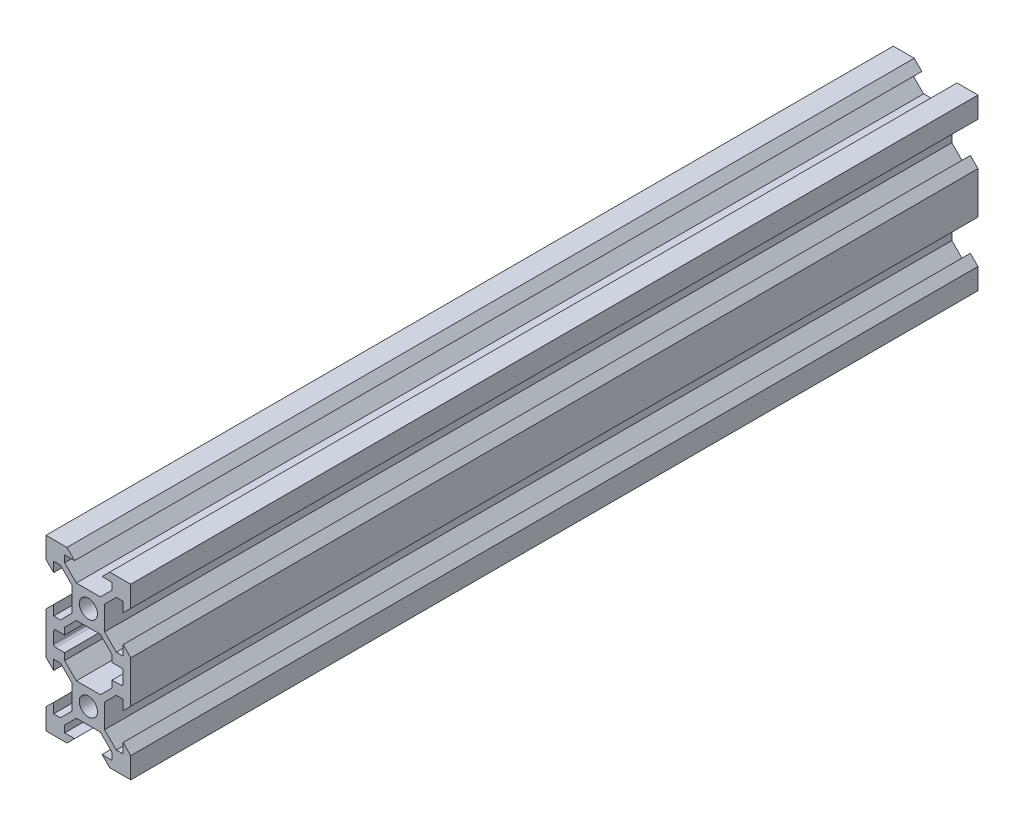
SolidWorks part; units mm, degrees
ref_plane "Alzado" through (0, 0, 0) normal (0, 0, 1) x (1, 0, 0)
ref_plane "Planta" through (0, 0, 0) normal (0, 1, 0) x (1, 0, 0)
ref_plane "Vista lateral" through (0, 0, 0) normal (1, 0, 0) x (0, 0, -1)
sketch "Croquis1" plane through (0, 0, 0) normal (0, 0, 1) x (1, 0, 0)
  line L0 (0, 0) -> (0, -20) construction
  line L2 (0, 0) -> (0, -0.5674)
  line L5 (6.175, -7.1649) -> (6.175, -12.8351)
  line L6 (7.1649, -13.825) -> (12.8351, -13.825)
  line L7 (13.825, -7.1649) -> (13.825, -12.8351)
  line L8 (7.1649, -6.175) -> (12.8351, -6.175)
  line L9 (6.175, -13.825) -> (13.825, -13.825) construction
  line L10 (13.825, -6.175) -> (13.825, -13.825) construction
  line L12 (10, -10) -> (32.1172, -10) construction
  line L13 (13.25, -18.2) -> (15.05, -20)
  line L14 (20, -20) -> (15.6, -20)
  line L15 (20, -20) -> (20, -15.6)
  line L16 (18.2, -15.6) -> (16.5899, -15.6)
  line L32 (15.6, -18.2) -> (15.6, -16.5899)
  line L33 (10, -10) -> (10, -23.2493) construction
  line L34 (4.4, -18.2) -> (4.4, -16.5899)
  line L35 (7.1649, -13.825) -> (4.4, -16.5899)
  line L36 (15.6, -18.2) -> (13.25, -18.2)
  line L38 (15.6, -20) -> (15.05, -20)
  line L40 (15.05, -20) -> (20, -20)
  line L41 (0, -20) -> (20, -20) construction
  line L42 (6.175, -12.8351) -> (3.4101, -15.6)
  line L43 (18.2, -13.25) -> (20, -15.05)
  line L44 (20, -20) -> (18.2, -20)
  line L45 (20, -20) -> (20, -15.05)
  line L48 (20, -15.05) -> (20, -20)
  line L49 (20, 0) -> (20, -20) construction
  line L50 (18.2, -15.6) -> (18.2, -13.25)
  line L51 (12.8351, -13.825) -> (15.6, -16.5899)
  line L52 (13.825, -12.8351) -> (16.5899, -15.6)
  line L53 (1.8, -15.6) -> (3.4101, -15.6)
  line L54 (1.8, -15.6) -> (1.8, -13.25)
  line L55 (1.8, -13.25) -> (0, -15.05)
  line L56 (0, 0) -> (20, 0) construction
  line L57 (0, -20) -> (0, -15.6)
  line L58 (0, -15.6) -> (0, -15.05)
  line L59 (0, -20) -> (4.4, -20)
  line L60 (0, -20) -> (4.95, -20)
  line L61 (6.75, -18.2) -> (4.95, -20)
  line L62 (4.4, -18.2) -> (6.75, -18.2)
  line L63 (1.8, -4.4) -> (3.4101, -4.4)
  line L64 (6.175, -7.1649) -> (3.4101, -4.4)
  line L65 (7.1649, -6.175) -> (4.4, -3.4101)
  line L66 (4.4, -1.8) -> (4.4, -3.4101)
  line L71 (0, 0) -> (0, -4.4)
  line L72 (0, 0) -> (0, -4.95)
  line L73 (1.8, -6.75) -> (0, -4.95)
  line L74 (1.8, -4.4) -> (1.8, -6.75)
  line L75 (15.6, -1.8) -> (15.6, -3.4101)
  line L76 (12.8351, -6.175) -> (15.6, -3.4101)
  line L77 (13.825, -7.1649) -> (16.5899, -4.4)
  line L78 (18.2, -4.4) -> (16.5899, -4.4)
  line L79 (18.2, -4.4) -> (18.2, -6.75)
  line L80 (18.2, -6.75) -> (20, -4.95)
  line L81 (20, 0) -> (20, -4.4)
  line L82 (20, -4.4) -> (20, -4.95)
  line L87 (6.175, -6.175) -> (13.825, -6.175) construction
  line L88 (6.175, -6.175) -> (6.175, -13.825) construction
  line L89 (0, 20) -> (0, 19.4326)
  line L90 (6.175, 12.8351) -> (6.175, 7.1649)
  line L91 (7.1649, 6.175) -> (12.8351, 6.175)
  line L92 (13.825, 12.8351) -> (13.825, 7.1649)
  line L93 (7.1649, 13.825) -> (12.8351, 13.825)
  line L96 (20, 0) -> (20, 4.4)
  line L97 (18.2, 4.4) -> (16.5899, 4.4)
  line L98 (15.6, 1.8) -> (15.6, 3.4101)
  line L99 (4.4, 1.8) -> (4.4, 3.4101)
  line L100 (7.1649, 6.175) -> (4.4, 3.4101)
  line L104 (6.175, 7.1649) -> (3.4101, 4.4)
  line L105 (18.2, 6.75) -> (20, 4.95)
  line L107 (20, 0) -> (20, 4.95)
  line L108 (20, 4.95) -> (20, 0)
  line L109 (18.2, 4.4) -> (18.2, 6.75)
  line L110 (12.8351, 6.175) -> (15.6, 3.4101)
  line L111 (13.825, 7.1649) -> (16.5899, 4.4)
  line L112 (1.8, 4.4) -> (3.4101, 4.4)
  line L113 (1.8, 4.4) -> (1.8, 6.75)
  line L114 (1.8, 6.75) -> (0, 4.95)
  line L115 (0, 0) -> (0, 4.4)
  line L116 (0, 4.4) -> (0, 4.95)
  line L121 (1.8, 15.6) -> (3.4101, 15.6)
  line L122 (6.175, 12.8351) -> (3.4101, 15.6)
  line L123 (7.1649, 13.825) -> (4.4, 16.5899)
  line L124 (4.4, 18.2) -> (4.4, 16.5899)
  line L125 (4.4, 18.2) -> (6.75, 18.2)
  line L126 (6.75, 18.2) -> (4.95, 20)
  line L127 (0, 20) -> (4.4, 20)
  line L128 (4.4, 20) -> (4.95, 20)
  line L129 (0, 20) -> (0, 15.6)
  line L130 (0, 20) -> (0, 15.05)
  line L131 (1.8, 13.25) -> (0, 15.05)
  line L132 (1.8, 15.6) -> (1.8, 13.25)
  line L133 (15.6, 18.2) -> (15.6, 16.5899)
  line L134 (12.8351, 13.825) -> (15.6, 16.5899)
  line L135 (13.825, 12.8351) -> (16.5899, 15.6)
  line L136 (18.2, 15.6) -> (16.5899, 15.6)
  line L137 (18.2, 15.6) -> (18.2, 13.25)
  line L138 (18.2, 13.25) -> (20, 15.05)
  line L139 (20, 20) -> (20, 15.6)
  line L140 (20, 15.6) -> (20, 15.05)
  line L141 (20, 20) -> (15.6, 20)
  line L142 (20, 20) -> (15.05, 20)
  line L143 (13.25, 18.2) -> (15.05, 20)
  line L144 (15.6, 18.2) -> (13.25, 18.2)
  line L146 (4.4, 1.8) -> (2.3, 1.8)
  line L147 (10, 10) -> (10, -3.2493) construction
  line L148 (10, 10) -> (32.1172, 10) construction
  line L150 (4.4, -1.8) -> (2.3, -1.8)
  line L151 (1.8, 1.3) -> (1.8, -1.3)
  line L152 (15.6, -1.8) -> (17.7, -1.8)
  line L154 (15.6, 1.8) -> (17.7, 1.8)
  line L155 (18.2, -1.3) -> (18.2, 1.3)
  line L156 (4.4, 1.8) -> (6.75, 1.8) [skipped]
  line L157 (6.75, 1.8) -> (4.95, 0) [skipped]
  line L158 (6.75, -1.8) -> (4.95, 0) [skipped]
  line L159 (4.4, -1.8) -> (6.75, -1.8) [skipped]
  line L160 (15.6, -1.8) -> (13.25, -1.8) [skipped]
  line L161 (13.25, -1.8) -> (15.05, 0) [skipped]
  line L162 (13.25, 1.8) -> (15.05, 0) [skipped]
  line L163 (15.6, 1.8) -> (13.25, 1.8) [skipped]
  line L164 (15.6, 0) -> (15.05, 0) [skipped]
  line L165 (4.4, 0) -> (4.95, 0) [skipped]
  line L166 (20, 0) -> (18.2, 0) [skipped]
  line L167 (18.2, 0) -> (20, 0) [skipped]
  line L168 (20, 0) -> (18.2, 0) [skipped]
  line L169 (20, 0) -> (18.2, 0) [skipped]
  line L170 (20, 0) -> (18.2, 0) [skipped]
  line L171 (0, 0) -> (1.8, 0) [skipped]
  line L172 (0, 0) -> (1.8, 0) [skipped]
  line L173 (0, 0) -> (1.8, 0) [skipped]
  circle A0 centre (10, -10) radius 2.15
  circle A1 centre (10, 10) radius 2.15
  arc A2 (17.7, 1.8) -> (18.2, 1.3) centre (17.7, 1.3) cw
  arc A3 (17.7, -1.8) -> (18.2, -1.3) centre (17.7, -1.3) ccw
  arc A4 (2.3, -1.8) -> (1.8, -1.3) centre (2.3, -1.3) cw
  arc A5 (2.3, 1.8) -> (1.8, 1.3) centre (2.3, 1.3) ccw
  point P69 (10, -10)
  point P128 (10, 10)
  dimension "D3" = 4.3
  dimension "D5" = 0.5
  dimension "D2" = 4
  dimension "D4" = 2
  dimension "D11" = 4.4
  dimension "D15" = 4.4
  dimension "D16" = 6.75
extrude "Saliente-Extruir1" add sketch "Croquis1" along normal blind 200 contours L144 L133 L134 L93 L123 L124 L125 L126 L128 L127 L89 L129 L130 L131 L132 L121 L122 L90 L104 L112 L113 L114 L116 L115 L2 L71 L72 L73 L74 L63 L64 L5 L42 L53 L54 L55 L58 L57 L59 L60 L61 L62 L34 L35 L6 L51 L32 L36 L13 L38 L40
